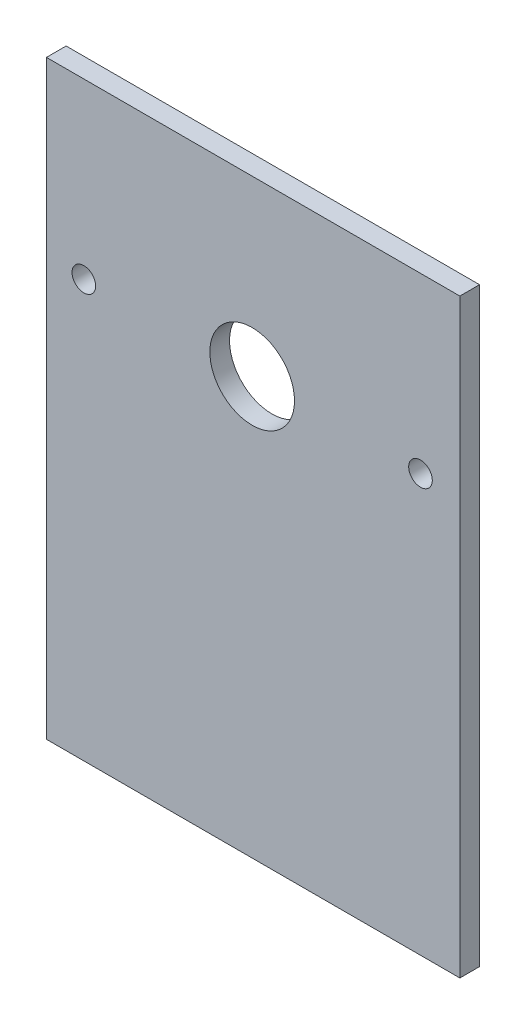
SolidWorks part; units mm, degrees
ref_plane "Front Plane" through (0, 0, 0) normal (0, 0, 1) x (1, 0, 0)
ref_plane "Top Plane" through (0, 0, 0) normal (0, 1, 0) x (1, 0, 0)
ref_plane "Right Plane" through (0, 0, 0) normal (1, 0, 0) x (0, 0, -1)
sketch "Sketch2" plane through (0, 0, 0) normal (0, 0, 1) x (1, 0, 0)
  line L1 (0, 0) -> (-105, 0)
  line L2 (0, 0) -> (0, -150)
  line L3 (0, -150) -> (-105, -150)
  line L4 (-105, 0) -> (-105, -150)
  dimension "D1" = 105
  dimension "D2" = 150
extrude "Boss-Extrude1" add sketch "Sketch2" along normal blind 5
sketch "Sketch3" plane through (0, 0, 5) normal (0, 0, 1) x (1, 0, 0)
  line L0 (0, -150) -> (0, 0) construction
  line L1 (0, 0) -> (-105, 0) construction
  circle A0 centre (-52.75, -44.05) radius 10.75
  circle A1 centre (-10, -44.05) radius 3
  circle A2 centre (-95.5, -44.05) radius 3
  point P6 (0, 0)
  dimension "D1" = 21.5
  dimension "D2" = 6
  dimension "D3" = 6
  dimension "D4" = 42.75
  dimension "D6" = 42.75
  dimension "D7" = 44.05
  dimension "D8" = 44.05
  dimension "D9" = 44.05
  dimension "D5" = 10
extrude "Cut-Extrude1" cut sketch "Sketch3" against normal up to surface (5 mm away) up to face at (-52.5, -75, 0)
